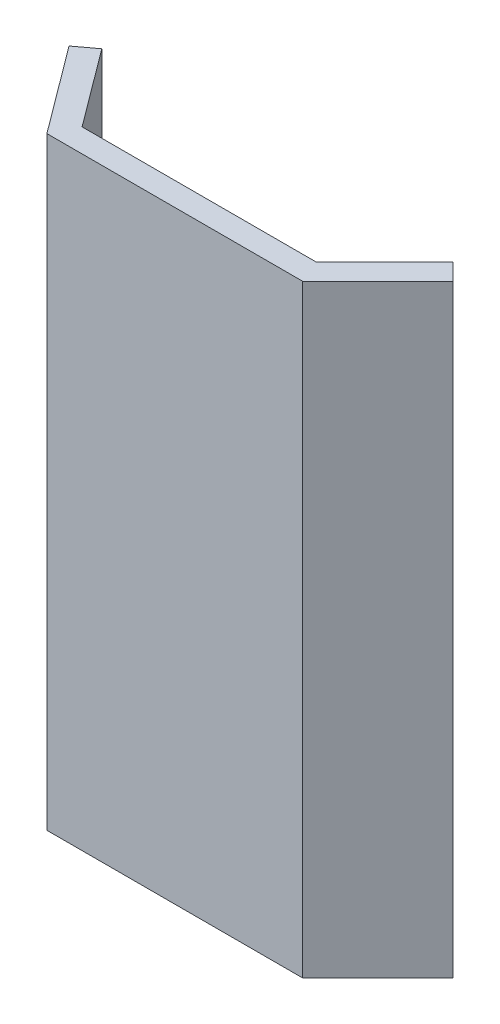
SolidWorks part; units mm, degrees
material "3.0205 (EN-AW 1200)"
ref_plane "Alzado" through (0, 0, 0) normal (0, 0, 1) x (1, 0, 0)
ref_plane "Planta" through (0, 0, 0) normal (0, 1, 0) x (1, 0, 0)
ref_plane "Vista lateral" through (0, 0, 0) normal (1, 0, 0) x (0, 0, -1)
sketch "Croquis1" plane through (0, 0, 0) normal (0, 1, 0) x (1, 0, 0)
  line L0 (-40, 0) -> (40, 0)
  line L1 (40, 0) -> (63.3345, 23.3345)
  line L2 (-40, 0) -> (-59.7181, 26.4612)
  line L3 (-44.0155, -8) -> (-66.133, 21.6811)
  line L4 (39.3244, -2.5006) -> (39.3244, 2.5006)
  line L5 (-44.0155, -8) -> (43.3137, -8)
  line L6 (43.3137, -8) -> (68.9914, 17.6777)
  line L7 (-66.133, 21.6811) -> (-59.7181, 26.4612)
  line L8 (63.3345, 23.3345) -> (68.9914, 17.6777)
  dimension "D1" = 33
  dimension "D2" = 33
  dimension "D3" = 8
  dimension "D4" = 80
extrude "Saliente-Extruir1" add sketch "Croquis1" along normal mid plane 206 contours L5 L6 L8 L1 L0 L2 L7 L3
sketch "Croquis2" plane through (0, 0, 0) normal (0, 0, -1) x (-1, 0, 0)
  line L0 (0, 0) -> (0, 103) construction
  line L1 (40, 103) -> (-40, 103) construction
  line L2 (34, -97) -> (34, -91)
  line L3 (-34, -97) -> (-24, -97)
  line L4 (-34, -97) -> (-34, -91)
  line L5 (-34, -91) -> (-24, -91)
  line L6 (-24, -97) -> (-24, -91)
  line L7 (34, -97) -> (24, -97)
  line L8 (24, -97) -> (24, -91)
  line L9 (34, -91) -> (24, -91)
  line L10 (-40, 103) -> (-40, -103) construction
  line L11 (40, -103) -> (-40, -103) construction
  dimension "D1" = 10
  dimension "D2" = 6
  dimension "D3" = 6
  dimension "D4" = 6
extrude "Saliente-Extruir2" add sketch "Croquis2" along normal blind 10
sketch "Croquis3" plane through (0, 0, 0) normal (0, 0, -1) x (-1, 0, 0)
  line L0 (-40, 0) -> (40, 0) construction
  line L1 (-40, 103) -> (-40, -103) construction
  line L2 (40, 103) -> (40, -103) construction
  line L3 (0, -103) -> (0, 103) construction
  line L4 (40, -103) -> (-40, -103) construction
  line L5 (40, 103) -> (-40, 103) construction
  line L7 (-24, -97) -> (-24, -91) construction
  line L10 (24, -91) -> (24, -97) construction
  circle A0 centre (-25.5, -64.6514) radius 1.5
  circle A1 centre (25.5, -65.6179) radius 1.5
  dimension "D1" = 3
  dimension "D2" = 3
  dimension "D3" = 51
sketch "Croquis8" plane through (0, -97, 0) normal (0, -1, 0) x (1, 0, 0)
  circle A0 centre (29, -5) radius 1.5
  circle A1 centre (-29, -5) radius 1.5
  dimension "D1" = 3
  dimension "D2" = 3
extrude "Cortar-Extruir3" cut sketch "Croquis8" against normal through all
